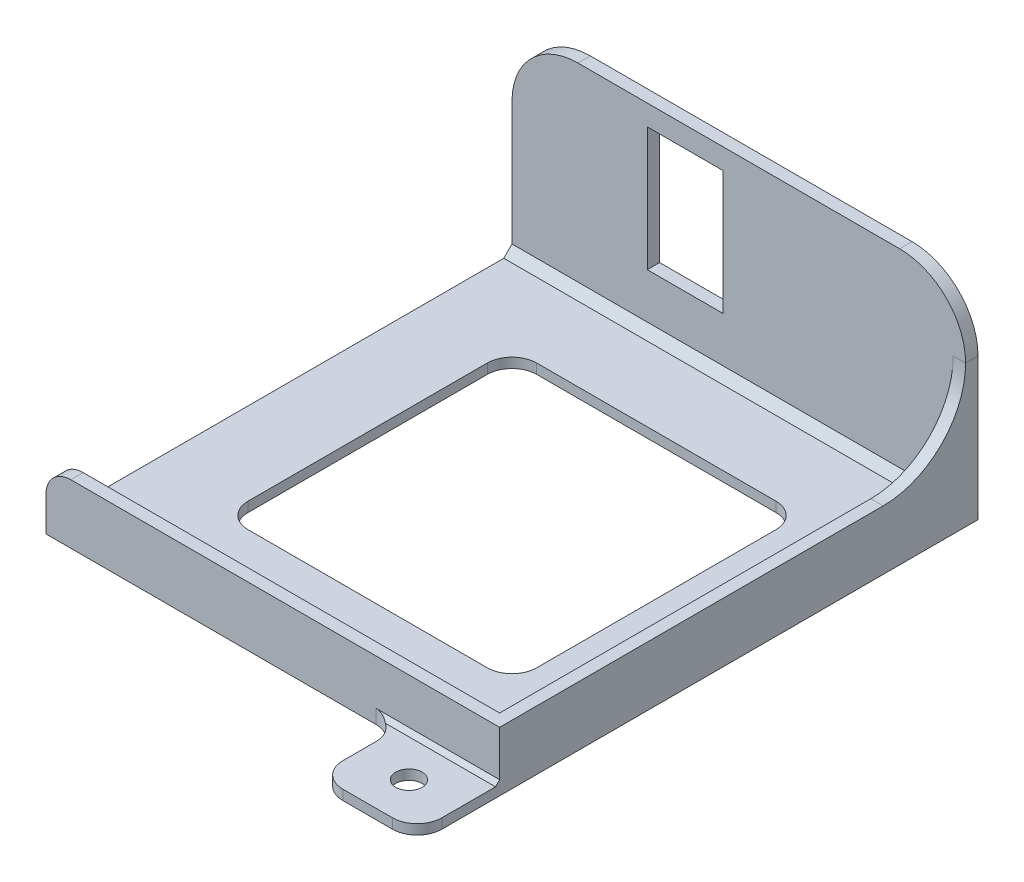
SolidWorks part; units mm, degrees
ref_plane "Plano frontal" through (0, 0, 0) normal (0, 0, 1) x (1, 0, 0)
ref_plane "Plano superior" through (0, 0, 0) normal (0, 1, 0) x (1, 0, 0)
ref_plane "Plano direito" through (0, 0, 0) normal (1, 0, 0) x (0, 0, -1)
sketch "Esboço1" plane through (0, 0, 0) normal (0, 1, 0) x (1, 0, 0)
  line L1 (-27.5, -29) -> (27.5, -29)
  line L2 (-27.5, -29) -> (-27.5, 29)
  line L3 (-27.5, 29) -> (27.5, 29)
  line L4 (27.5, -29) -> (27.5, 29)
  line L5 (-27.5, -29) -> (27.5, 29) construction
  line L6 (-27.5, 29) -> (27.5, -29) construction
  point P0 (0, 0)
  dimension "D1" = 55
  dimension "D2" = 58
extrude "Base" add sketch "Esboço1" along normal blind 1.2
sketch "Esboço2" plane through (0, 1.2, 0) normal (0, 1, 0) x (1, 0, 0)
  line L0 (-27.5, 29) -> (-27.5, -29) construction
  line L1 (-27.5, -29) -> (27.5, -29) construction
  line L2 (27.5, -29) -> (27.5, 29) construction
  line L3 (27.5, 29) -> (-27.5, 29) construction
  line L4 (-27.5, 29) -> (-27.5, -29)
  line L5 (-27.5, -29) -> (27.5, -29)
  line L6 (27.5, -29) -> (27.5, 29)
  line L7 (27.5, 29) -> (-27.5, 29)
  line L8 (26, 27.5) -> (-26, 27.5)
  line L9 (-26, 27.5) -> (-26, -27.5)
  line L10 (-26, -27.5) -> (26, -27.5)
  line L11 (26, -27.5) -> (26, 27.5)
  dimension "D1" = 1.5
extrude "Paredes" add sketch "Esboço2" along normal blind 24
sketch "Esboço3" plane through (0, 25.2, 0) normal (0, 1, 0) x (1, 0, 0)
  line L0 (-27.5, 29) -> (-27.5, -29) construction
  line L1 (-29.986, -27.5) -> (-25.014, -27.5)
  line L2 (-29.986, -27.5) -> (-29.986, 27.5)
  line L3 (-29.986, 27.5) -> (-25.014, 27.5)
  line L4 (-25.014, -27.5) -> (-25.014, 27.5)
  line L5 (-29.986, -27.5) -> (-25.014, 27.5) construction
  line L6 (-29.986, 27.5) -> (-25.014, -27.5) construction
  line L7 (26, 27.5) -> (-26, 27.5) construction
  point P0 (-27.5, 0)
extrude "Corte-extrusão1" cut sketch "Esboço3" against normal up to surface (24 mm away) up to face at (0, 1.2, 0)
sketch "Esboço4" plane through (0, 0, -29) normal (0, 0, -1) x (-1, 0, 0)
  line L0 (-27.5, 25.2) -> (-27.5, 0) construction
  line L1 (1.9, 7.7) -> (11.1, 7.7)
  line L2 (1.9, 7.7) -> (1.9, 22.7)
  line L3 (1.9, 22.7) -> (11.1, 22.7)
  line L4 (11.1, 7.7) -> (11.1, 22.7)
  line L5 (1.9, 7.7) -> (11.1, 22.7) construction
  line L6 (1.9, 22.7) -> (11.1, 7.7) construction
  line L7 (-27.5, 0) -> (27.5, 0) construction
  point P0 (6.5, 15.2)
  point P7 (0, 0)
  point P9 (-27.4596, 0)
  point P12 (13.0775, -1.2344)
  dimension "D1" = 9.2
  dimension "D2" = 15
  dimension "D3" = 34
  dimension "D4" = 15.2
extrude "Encaixe chave" cut sketch "Esboço4" against normal blind 17
sketch "Esboço5" plane through (-27.5, 0, 0) normal (-1, 0, 0) x (0, 0, 1)
  line L0 (29, 25.2) -> (29, 0) construction
  line L1 (27.5, 25.2) -> (29, 25.2)
  line L2 (27.5, 25.2) -> (27.5, 7.2)
  line L3 (27.5, 7.2) -> (29, 7.2)
  line L4 (29, 25.2) -> (29, 7.2)
  dimension "D1" = 18
extrude "Corte-extrusão3" cut sketch "Esboço5" against normal through all
fillet "Filete1" radius 8 1 edges at (-27.5, 25.2, -28.25)
fillet "Filete2" radius 3 1 edges at (-27.5, 7.2, 28.25)
chamfer "Chanfro1" distance 1 angle 45 3 edges at (-0.75, 1.2, 27.5) (26, 1.2, 0) (-0.75, 1.2, -27.5)
sketch "Esboço7" plane through (0, 1.2, 0) normal (0, 1, 0) x (1, 0, 0)
  line L1 (-14.5, -17.5) -> (14.5, -17.5)
  line L2 (-17.5, -14.5) -> (-17.5, 14.5)
  line L3 (-14.5, 17.5) -> (14.5, 17.5)
  line L4 (17.5, -14.5) -> (17.5, 14.5)
  line L5 (-17.5, -17.5) -> (17.5, 17.5) construction
  line L6 (-17.5, 17.5) -> (17.5, -17.5) construction
  arc A0 (14.5, 17.5) -> (17.5, 14.5) centre (14.5, 14.5) cw
  arc A1 (17.5, -14.5) -> (14.5, -17.5) centre (14.5, -14.5) cw
  arc A2 (-14.5, -17.5) -> (-17.5, -14.5) centre (-14.5, -14.5) cw
  arc A3 (-14.5, 17.5) -> (-17.5, 14.5) centre (-14.5, 14.5) ccw
  point P0 (0, 0)
  dimension "D3" = 3
  dimension "D1" = 35
  dimension "D2" = 35
extrude "Corte-extrusão5" cut sketch "Esboço7" against normal blind 17
sketch "Esboço8" plane through (27.5, 0, 0) normal (1, 0, 0) x (0, 0, -1)
  line L1 (-27.5, 25.2) -> (27.5, 25.2)
  line L2 (-27.5, 25.2) -> (-27.5, 7.2)
  line L3 (-27.5, 7.2) -> (27.5, 7.2)
  line L4 (27.5, 25.2) -> (27.5, 7.2)
  dimension "D1" = 18
  dimension "D2" = 55
extrude "Corte-extrusão6" cut sketch "Esboço8" against normal blind 17
fillet "Filete6" radius 8 1 edges at (27.5, 25.2, -28.25)
fillet "Filete7" radius 10 2 edges at (26.75, 7.2, -27.5) (27.5, 12.2, -27.5)
sketch "Esboço9" plane through (0, 0, 29) normal (0, 0, 1) x (1, 0, 0)
  line L1 (27.5, 0) -> (15.5, 0)
  line L2 (27.5, 0) -> (27.5, 1.2)
  line L3 (27.5, 1.2) -> (15.5, 1.2)
  line L4 (15.5, 0) -> (15.5, 1.2)
  dimension "D1" = 1.2
  dimension "D2" = 12
extrude "Ressalto-extrusão3" add sketch "Esboço9" along normal blind 10
sketch "Esboço10" plane through (0, 1.2, 0) normal (0, 1, 0) x (1, 0, 0)
  line L0 (27.5, -39) -> (27.5, -29) construction
  line L1 (27.5, -29) -> (-24.5, -29) construction
  circle A0 centre (21.5, -34) radius 1.6
  dimension "D1" = 3.2
  dimension "D2" = 6
  dimension "D3" = 5
extrude "Corte-extrusão7" cut sketch "Esboço10" against normal blind 10
fillet "Filete8" radius 3 1 edges at (15.5, 0.6, 39)
fillet "Filete9" radius 3 1 edges at (27.5, 0.6, 39)
fillet "Filete10" radius 3 1 edges at (15.5, 0.6, 29)
chamfer "Chanfro2" distance 0.5 angle 45 1 edges at (20, 1.2, 29)
